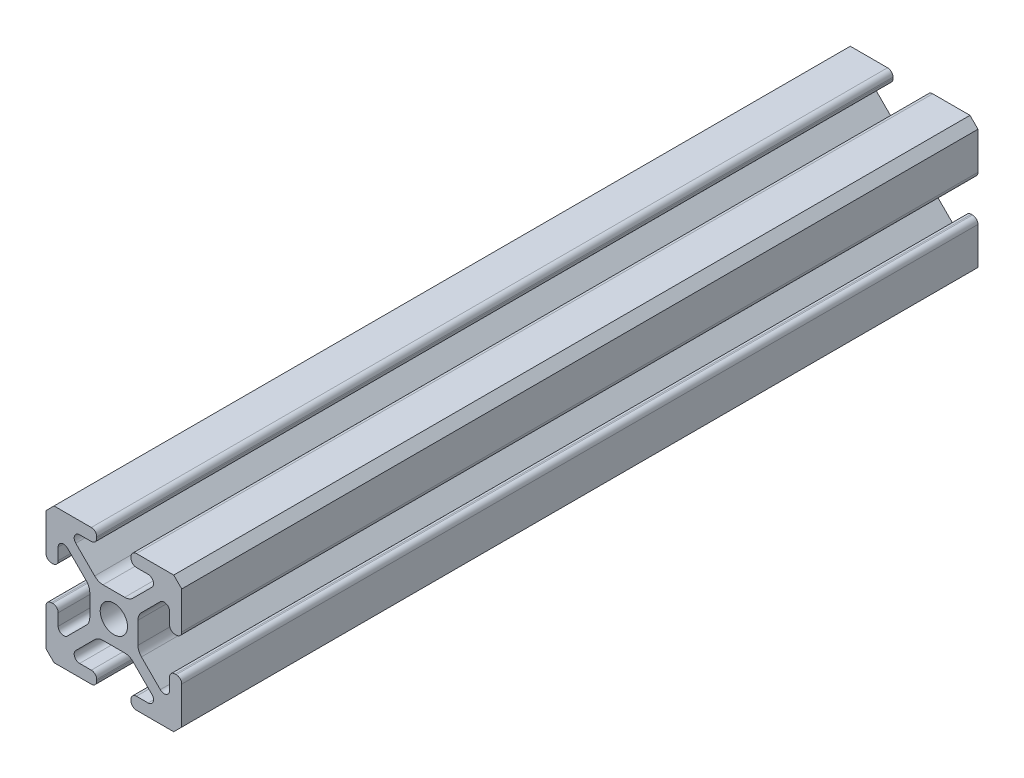
SolidWorks part; units mm, degrees
ref_plane "Front Plane" through (0, 0, 0) normal (0, 0, 1) x (1, 0, 0)
ref_plane "Top Plane" through (0, 0, 0) normal (0, 1, 0) x (1, 0, 0)
ref_plane "Right Plane" through (0, 0, 0) normal (1, 0, 0) x (0, 0, -1)
other "Configuration Table"
sketch "Sketch1" plane through (0, 0, 0) normal (0, 0, 1) x (1, 0, 0)
  line L0 (-11.2, -12.7) -> (-4.2223, -12.7)
  line L1 (-3.2063, -11.684) -> (-3.2063, -11.4407)
  line L2 (-4.2223, -10.4247) -> (-6.4093, -10.4247)
  line L3 (-7.1277, -8.6902) -> (-3.5932, -5.1557)
  line L4 (-2.0306, -4.5085) -> (2.0306, -4.5085)
  line L5 (3.5932, -5.1557) -> (7.1277, -8.6902)
  line L6 (6.4093, -10.4247) -> (4.2223, -10.4247)
  line L7 (3.2063, -11.4407) -> (3.2063, -11.684)
  line L8 (4.2223, -12.7) -> (11.2, -12.7)
  line L9 (11.2, -12.7) -> (12.7, -11.2)
  line L10 (12.7, -11.2) -> (12.7, -4.2223)
  line L11 (11.684, -3.2063) -> (11.4407, -3.2063)
  line L12 (10.4247, -4.2223) -> (10.4247, -6.4093)
  line L13 (8.6902, -7.1277) -> (5.1557, -3.5932)
  line L14 (4.5085, -2.0306) -> (4.5085, 2.0306)
  line L15 (5.1557, 3.5932) -> (8.6902, 7.1277)
  line L16 (10.4247, 6.4093) -> (10.4247, 4.2223)
  line L17 (11.4407, 3.2063) -> (11.684, 3.2063)
  line L18 (12.7, 4.2223) -> (12.7, 11.2)
  line L19 (12.7, 11.2) -> (11.2, 12.7)
  line L20 (11.2, 12.7) -> (4.2223, 12.7)
  line L21 (3.2063, 11.684) -> (3.2063, 11.4407)
  line L22 (4.2223, 10.4247) -> (6.4093, 10.4247)
  line L23 (7.1277, 8.6902) -> (3.5932, 5.1557)
  line L24 (2.0306, 4.5085) -> (-2.0306, 4.5085)
  line L25 (-3.5932, 5.1557) -> (-7.1277, 8.6902)
  line L26 (-6.4093, 10.4247) -> (-4.2223, 10.4247)
  line L27 (-3.2063, 11.4407) -> (-3.2063, 11.684)
  line L28 (-4.2223, 12.7) -> (-11.2, 12.7)
  line L29 (-11.2, 12.7) -> (-12.7, 11.2)
  line L30 (-12.7, 11.2) -> (-12.7, 4.2223)
  line L31 (-11.684, 3.2063) -> (-11.4407, 3.2063)
  line L32 (-10.4247, 4.2223) -> (-10.4247, 6.4093)
  line L33 (-8.6902, 7.1277) -> (-5.1557, 3.5932)
  line L34 (-4.5085, 2.0306) -> (-4.5085, -2.0306)
  line L35 (-5.1557, -3.5932) -> (-8.6902, -7.1277)
  line L36 (-10.4247, -6.4093) -> (-10.4247, -4.2223)
  line L37 (-11.4407, -3.2063) -> (-11.684, -3.2063)
  line L38 (-12.7, -4.2223) -> (-12.7, -11.2)
  line L39 (-12.7, -11.2) -> (-11.2, -12.7)
  arc A0 (-2.555, 0) -> (2.555, 0) centre (0, 0) ccw
  arc A1 (2.555, 0) -> (-2.555, 0) centre (0, 0) ccw
  arc A2 (-4.2223, -12.7) -> (-3.2063, -11.684) centre (-4.2223, -11.684) ccw
  arc A3 (-3.2063, -11.4407) -> (-4.2223, -10.4247) centre (-4.2223, -11.4407) ccw
  arc A4 (-7.1277, -8.6902) -> (-6.4093, -10.4247) centre (-6.4093, -9.4087) ccw
  arc A5 (-2.0306, -4.5085) -> (-3.5932, -5.1557) centre (-2.0306, -6.7183) ccw
  arc A6 (3.5932, -5.1557) -> (2.0306, -4.5085) centre (2.0306, -6.7183) ccw
  arc A7 (7.4253, -9.4087) -> (7.1277, -8.6902) centre (6.4093, -9.4087) ccw
  arc A8 (6.4093, -10.4247) -> (7.4253, -9.4087) centre (6.4093, -9.4087) ccw
  arc A9 (4.2223, -10.4247) -> (3.2063, -11.4407) centre (4.2223, -11.4407) ccw
  arc A10 (3.2063, -11.684) -> (4.2223, -12.7) centre (4.2223, -11.684) ccw
  arc A11 (12.7, -4.2223) -> (11.684, -3.2063) centre (11.684, -4.2223) ccw
  arc A12 (11.4407, -3.2063) -> (10.4247, -4.2223) centre (11.4407, -4.2223) ccw
  arc A13 (8.6902, -7.1277) -> (10.4247, -6.4093) centre (9.4087, -6.4093) ccw
  arc A14 (4.5085, -2.0306) -> (5.1557, -3.5932) centre (6.7183, -2.0306) ccw
  arc A15 (5.1557, 3.5932) -> (4.5085, 2.0306) centre (6.7183, 2.0306) ccw
  arc A16 (9.4087, 7.4253) -> (8.6902, 7.1277) centre (9.4087, 6.4093) ccw
  arc A17 (10.4247, 6.4093) -> (9.4087, 7.4253) centre (9.4087, 6.4093) ccw
  arc A18 (10.4247, 4.2223) -> (11.4407, 3.2063) centre (11.4407, 4.2223) ccw
  arc A19 (11.684, 3.2063) -> (12.7, 4.2223) centre (11.684, 4.2223) ccw
  arc A20 (4.2223, 12.7) -> (3.2063, 11.684) centre (4.2223, 11.684) ccw
  arc A21 (3.2063, 11.4407) -> (4.2223, 10.4247) centre (4.2223, 11.4407) ccw
  arc A22 (7.1277, 8.6902) -> (6.4093, 10.4247) centre (6.4093, 9.4087) ccw
  arc A23 (2.0306, 4.5085) -> (3.5932, 5.1557) centre (2.0306, 6.7183) ccw
  arc A24 (-3.5932, 5.1557) -> (-2.0306, 4.5085) centre (-2.0306, 6.7183) ccw
  arc A25 (-7.4253, 9.4087) -> (-7.1277, 8.6902) centre (-6.4093, 9.4087) ccw
  arc A26 (-6.4093, 10.4247) -> (-7.4253, 9.4087) centre (-6.4093, 9.4087) ccw
  arc A27 (-4.2223, 10.4247) -> (-3.2063, 11.4407) centre (-4.2223, 11.4407) ccw
  arc A28 (-3.2063, 11.684) -> (-4.2223, 12.7) centre (-4.2223, 11.684) ccw
  arc A29 (-12.7, 4.2223) -> (-11.684, 3.2063) centre (-11.684, 4.2223) ccw
  arc A30 (-11.4407, 3.2063) -> (-10.4247, 4.2223) centre (-11.4407, 4.2223) ccw
  arc A31 (-8.6902, 7.1277) -> (-10.4247, 6.4093) centre (-9.4087, 6.4093) ccw
  arc A32 (-4.5085, 2.0306) -> (-5.1557, 3.5932) centre (-6.7183, 2.0306) ccw
  arc A33 (-5.1557, -3.5932) -> (-4.5085, -2.0306) centre (-6.7183, -2.0306) ccw
  arc A34 (-9.4087, -7.4253) -> (-8.6902, -7.1277) centre (-9.4087, -6.4093) ccw
  arc A35 (-10.4247, -6.4093) -> (-9.4087, -7.4253) centre (-9.4087, -6.4093) ccw
  arc A36 (-10.4247, -4.2223) -> (-11.4407, -3.2063) centre (-11.4407, -4.2223) ccw
  arc A37 (-11.684, -3.2063) -> (-12.7, -4.2223) centre (-11.684, -4.2223) ccw
extrude "Boss-Extrude1" add sketch "Sketch1" along normal blind 149
equation "\"Extrusion Length\"= 24"
